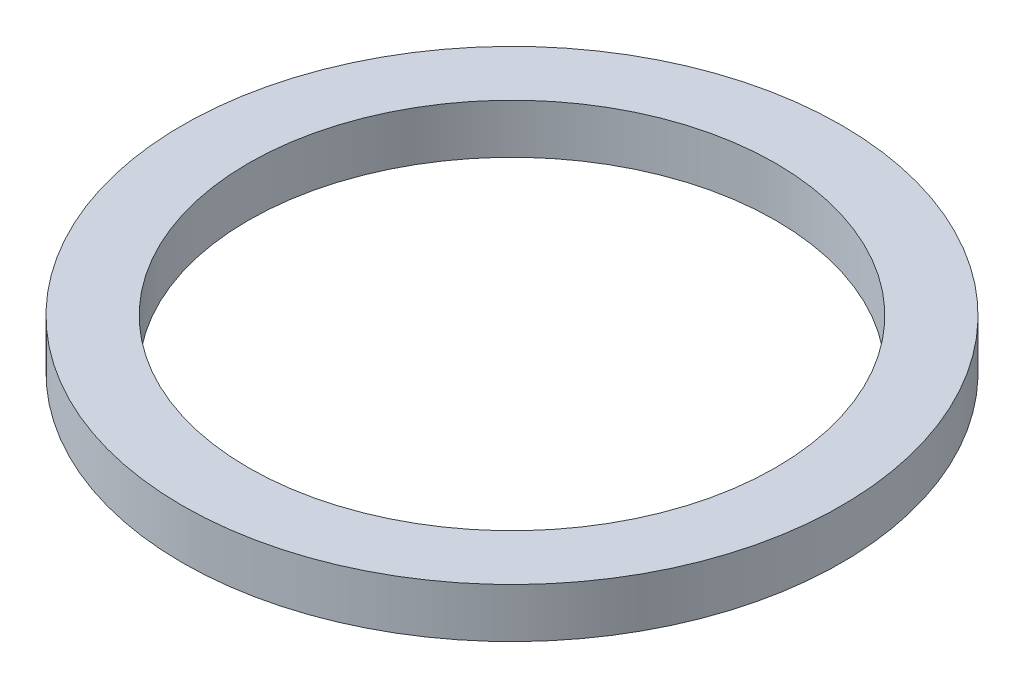
SolidWorks part; units mm, degrees
ref_plane "Plan de face" through (0, 0, 0) normal (0, 0, 1) x (1, 0, 0)
ref_plane "Plan de dessus" through (0, 0, 0) normal (0, 1, 0) x (1, 0, 0)
ref_plane "Plan de droite" through (0, 0, 0) normal (1, 0, 0) x (0, 0, -1)
sketch "Esquisse1" plane through (0, 0, 0) normal (0, 1, 0) x (1, 0, 0)
  circle A0 centre (0, 0) radius 4
  circle A1 centre (0, 0) radius 5
  dimension "D1" = 10
  dimension "D2" = 8
extrude "Boss.-Extru.1" add sketch "Esquisse1" along normal blind 0.75
